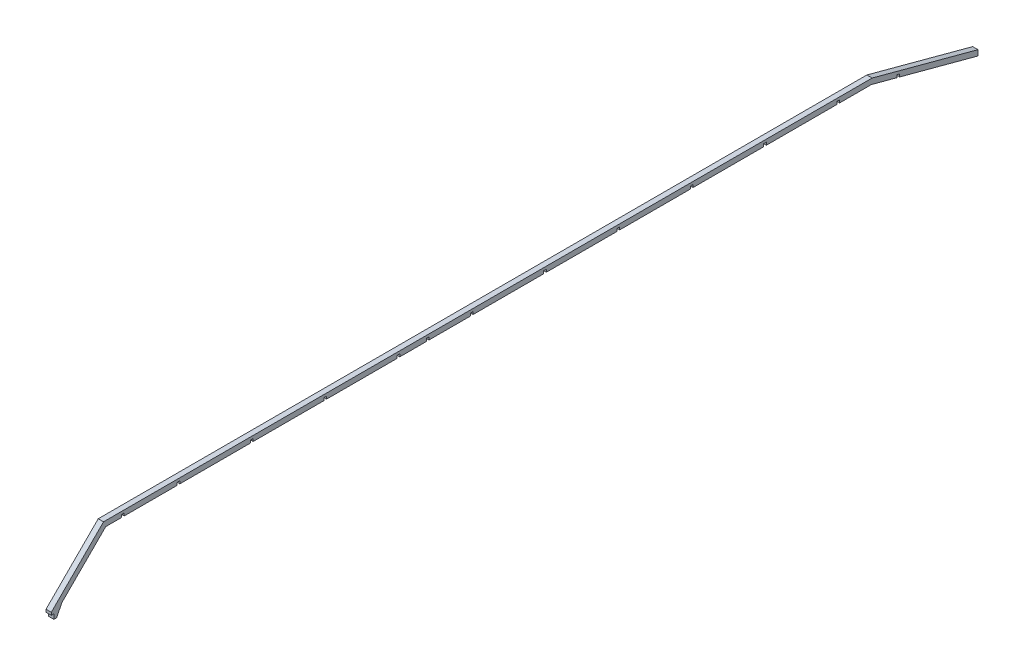
SolidWorks part; units mm, degrees
ref_plane "Спереди" through (0, 0, 0) normal (0, 0, 1) x (1, 0, 0)
ref_plane "Сверху" through (0, 0, 0) normal (0, 1, 0) x (1, 0, 0)
ref_plane "Справа" through (0, 0, 0) normal (1, 0, 0) x (0, 0, -1)
other "Configuration Table"
sketch "Эскиз1" plane through (0, 0, 0) normal (1, 0, 0) x (0, 0, -1)
  line L0 (-751.8866, -19.1422) -> (-733.9606, -19.1422)
  line L1 (115.1734, -19.1422) -> (144.0394, -26.8768)
  line L6 (161.6151, -31.5862) -> (163.168, -25.7906) construction
  line L7 (-813.5251, -80.7807) -> (-751.8866, -19.1422) construction
  line L8 (-813.5251, -72.2954) -> (-813.5251, -80.7807) construction
  line L17 (147.0394, -27.6806) -> (147.0394, -24.6806)
  line L18 (147.0394, -24.6806) -> (144.0394, -23.8768)
  line L19 (144.0394, -23.8768) -> (144.0394, -26.8768)
  line L20 (147.0394, -27.6806) -> (235.7903, -51.4614)
  line L21 (79.0394, -19.1422) -> (79.0394, -16.1422)
  line L22 (79.0394, -16.1422) -> (76.0394, -16.1422)
  line L23 (76.0394, -16.1422) -> (76.0394, -19.1422)
  line L24 (79.0394, -19.1422) -> (115.1734, -19.1422)
  line L25 (-3.9606, -19.1422) -> (-3.9606, -16.1422)
  line L26 (-3.9606, -16.1422) -> (-6.9606, -16.1422)
  line L27 (-6.9606, -16.1422) -> (-6.9606, -19.1422)
  line L28 (-86.9606, -19.1422) -> (-86.9606, -16.1422)
  line L29 (-86.9606, -16.1422) -> (-89.9606, -16.1422)
  line L30 (-89.9606, -16.1422) -> (-89.9606, -19.1422)
  line L31 (-169.9606, -19.1422) -> (-169.9606, -16.1422)
  line L32 (-169.9606, -16.1422) -> (-172.9606, -16.1422)
  line L33 (-172.9606, -16.1422) -> (-172.9606, -19.1422)
  line L34 (-252.9606, -19.1422) -> (-252.9606, -16.1422)
  line L35 (-252.9606, -16.1422) -> (-255.9606, -16.1422)
  line L36 (-255.9606, -16.1422) -> (-255.9606, -19.1422)
  line L37 (-335.9606, -19.1422) -> (-335.9606, -16.1422)
  line L38 (-335.9606, -16.1422) -> (-338.9606, -16.1422)
  line L39 (-338.9606, -16.1422) -> (-338.9606, -19.1422)
  line L40 (-3.9606, -19.1422) -> (76.0394, -19.1422)
  line L41 (-86.9606, -19.1422) -> (-6.9606, -19.1422)
  line L42 (-169.9606, -19.1422) -> (-89.9606, -19.1422)
  line L43 (-252.9606, -19.1422) -> (-172.9606, -19.1422)
  line L44 (-335.9606, -19.1422) -> (-255.9606, -19.1422)
  line L45 (-385.9606, -19.1422) -> (-385.9606, -16.1422)
  line L46 (-385.9606, -16.1422) -> (-388.9606, -16.1422)
  line L47 (-388.9606, -16.1422) -> (-388.9606, -19.1422)
  line L48 (-385.9606, -19.1422) -> (-338.9606, -19.1422)
  line L49 (-418.9606, -19.1422) -> (-418.9606, -16.1422)
  line L50 (-418.9606, -16.1422) -> (-421.9606, -16.1422)
  line L51 (-421.9606, -16.1422) -> (-421.9606, -19.1422)
  line L52 (-418.9606, -19.1422) -> (-388.9606, -19.1422)
  line L53 (-501.9606, -19.1422) -> (-501.9606, -16.1422)
  line L54 (-501.9606, -16.1422) -> (-504.9606, -16.1422)
  line L55 (-504.9606, -16.1422) -> (-504.9606, -19.1422)
  line L56 (-584.9606, -19.1422) -> (-584.9606, -16.1422)
  line L57 (-584.9606, -16.1422) -> (-587.9606, -16.1422)
  line L58 (-587.9606, -16.1422) -> (-587.9606, -19.1422)
  line L59 (-667.9606, -19.1422) -> (-667.9606, -16.1422)
  line L60 (-667.9606, -16.1422) -> (-670.9606, -16.1422)
  line L61 (-670.9606, -16.1422) -> (-670.9606, -19.1422)
  line L62 (-501.9606, -19.1422) -> (-421.9606, -19.1422)
  line L63 (-584.9606, -19.1422) -> (-504.9606, -19.1422)
  line L64 (-667.9606, -19.1422) -> (-587.9606, -19.1422)
  line L65 (-730.9606, -19.1422) -> (-730.9606, -16.1422)
  line L66 (-730.9606, -16.1422) -> (-733.9606, -16.1422)
  line L67 (-733.9606, -16.1422) -> (-733.9606, -19.1422)
  line L68 (-730.9606, -19.1422) -> (-670.9606, -19.1422)
  line L69 (235.7903, -51.4614) -> (237.3432, -45.6658) construction
  line L70 (-3.9606, -19.1422) -> (-3.9606, -13.1422) construction
  line L71 (163.168, -25.7906) -> (80.8644, -3.7374) construction
  line L72 (237.3432, -45.6658) -> (163.168, -25.7906) construction
  line L73 (79.0394, -19.1422) -> (79.0394, -13.1422) construction
  line L74 (235.7903, -51.4614) -> (235.7903, -45.2497)
  line L75 (-3.9606, -13.1422) -> (115.9633, -13.1422) construction
  line L76 (-803.8198, -71.0753) -> (-808.0624, -66.8327) construction
  line L77 (-751.8866, -19.1422) -> (-756.1293, -14.8995) construction
  line L78 (-3.9606, -13.1422) -> (-770.7331, -13.1422) construction
  line L79 (-756.1293, -14.8995) -> (-813.5251, -72.2954) construction
  line L81 (-810.5251, -80.7807) -> (-807.5251, -80.7807)
  line L82 (-807.5251, -80.7807) -> (-801.5251, -80.7807) construction
  line L83 (-801.5251, -80.7807) -> (-801.5251, -68.7807) construction
  line L84 (-807.5251, -80.7807) -> (-801.5251, -68.7807)
  line L85 (-801.5251, -68.7807) -> (-751.8866, -19.1422)
  line L86 (-813.5251, -72.2954) -> (-754.3719, -13.1422)
  line L87 (-754.3719, -13.1422) -> (115.9633, -13.1422)
  line L88 (115.9633, -13.1422) -> (235.7903, -45.2497)
  line L89 (-813.5251, -72.2954) -> (-813.5251, -75.2954)
  line L90 (-813.5251, -75.2954) -> (-810.5251, -75.2954)
  line L91 (-810.5251, -75.2954) -> (-810.5251, -80.7807)
  point P49 (-388.9606, -17.6422)
  dimension "D4" = 6
  dimension "D5" = 6
  dimension "D6" = 867.06
  dimension "D7" = 6
  dimension "D8" = 3
  dimension "D9" = 3
  dimension "D10" = 6
  dimension "D11" = 81.17
  dimension "D12" = 3
  dimension "D13" = 65
  dimension "D14" = 3
  dimension "D15" = 3
  dimension "D16" = 3
  dimension "D17" = 80
  dimension "D18" = 3
  dimension "D19" = 80
  dimension "D20" = 3
  dimension "D21" = 80
  dimension "D22" = 3
  dimension "D23" = 80
  dimension "D24" = 3
  dimension "D25" = 80
  dimension "D26" = 3
  dimension "D27" = 47
  dimension "D28" = 3
  dimension "D29" = 3
  dimension "D30" = 30
  dimension "D31" = 3
  dimension "D32" = 80
  dimension "D33" = 3
  dimension "D34" = 80
  dimension "D35" = 80
  dimension "D36" = 3
  dimension "D37" = 3
  dimension "D38" = 60
  dimension "D39" = 6
  dimension "D40" = 6
  dimension "D41" = 119.827
  dimension "D42" = 15
extrude "Бобышка-Вытянуть3" add sketch "Эскиз1" along normal blind 6
